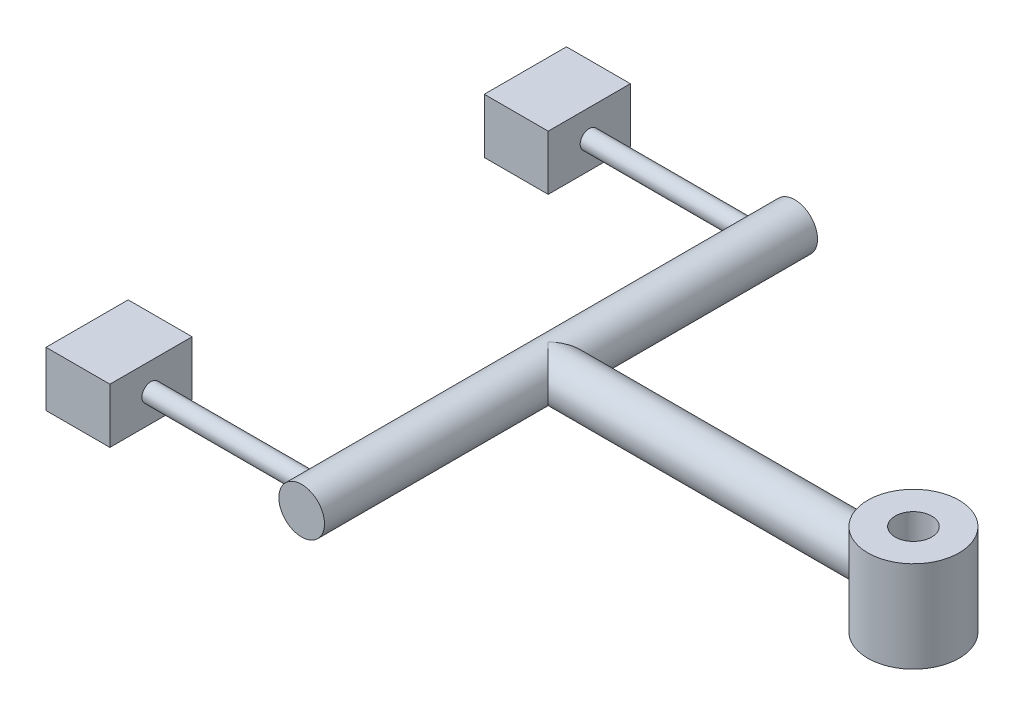
SolidWorks part; units mm, degrees
ref_plane "Front Plane" through (0, 0, 0) normal (0, 0, 1) x (1, 0, 0)
ref_plane "Top Plane" through (0, 0, 0) normal (0, 1, 0) x (1, 0, 0)
ref_plane "Right Plane" through (0, 0, 0) normal (1, 0, 0) x (0, 0, -1)
sketch "Sketch1" plane through (0, 0, 0) normal (0, 1, 0) x (1, 0, 0)
  line L7 (-350, 0) -> (50, 0)
  line L8 (-350, 0) -> (-350, -25)
  line L9 (-350, -25) -> (50, -25)
  line L10 (50, 0) -> (50, -25)
  point P0 (0, 12.5)
  dimension "D1" = 400
  dimension "D3" = 25
revolve "Revolve1" add sketch "Sketch1" angle 360 about L7
sketch "Sketch2" plane through (0, 0, 0) normal (0, 1, 0) x (1, 0, 0)
  line L1 (-350, -270) -> (-375, -270)
  line L2 (-350, -270) -> (-350, 270)
  line L3 (-350, 270) -> (-375, 270)
  line L4 (-375, -270) -> (-375, 270)
  line L5 (-350, -270) -> (-375, 270) construction
  line L6 (-350, 270) -> (-375, -270) construction
  line L7 (-322.6011, 25) -> (-322.6011, -25) construction
  line L10 (50, 25) -> (-350, 25) construction
  line L11 (-350, -25) -> (50, -25) construction
  line L12 (-322.6011, 0) -> (-375, 0) construction
  point P0 (-362.5, 0)
  dimension "D1" = 540
  dimension "D2" = 25
revolve "Revolve2" add sketch "Sketch2" angle 360 about L2
sketch "Sketch4" plane through (0, 0, 0) normal (0, 1, 0) x (1, 0, 0)
  line L0 (50, -25) -> (50, 25) construction
  line L1 (50, 25) -> (50, -25) construction
  line L2 (50, 25) -> (-325, 25) construction
  line L3 (-325, -25) -> (50, -25) construction
  circle A0 centre (50, 0) radius 50
  point P11 (50, 0)
  dimension "D1" = 100
extrude "Boss-Extrude1" add sketch "Sketch4" along normal mid plane 100
sketch "Sketch5" plane through (0, 0, 0) normal (0, 1, 0) x (1, 0, 0)
  line L0 (-350, 240) -> (-550, 240)
  line L1 (-350, -240) -> (-550, -240)
  line L2 (-350, 240) -> (-350, -240) construction
  line L3 (-350, 0) -> (-588.5917, 0) construction
  line L6 (-350, 265) -> (-350, 240) construction
  line L9 (-350, 240) -> (-350, -252.5) construction
  line L11 (-350, 240) -> (-350, 265)
  line L12 (-350, 265) -> (-550, 265)
  line L13 (-550, 240) -> (-550, 265)
  line L14 (-450, 240) -> (-550, 265) construction
  line L15 (-350, 265) -> (-450, 240) construction
  line L16 (-550, -227.5) -> (-350, -227.5)
  line L17 (-550, -227.5) -> (-550, -252.5)
  line L18 (-550, -252.5) -> (-350, -252.5)
  line L19 (-350, -227.5) -> (-350, -252.5)
  line L20 (-550, -227.5) -> (-350, -252.5) construction
  line L21 (-550, -252.5) -> (-350, -227.5) construction
  point P18 (-450, 240)
  point P22 (-450, -240)
  dimension "D1" = 240
  dimension "D2" = 200
  dimension "D3" = 200
  dimension "D4" = 25
  dimension "D5" = 25
revolve "Revolve-Thin1" add sketch "Sketch5" angle 360 about L0
mirror "Mirror2" about plane through (0, 0, 0) normal (0, 0, 1) of "Revolve-Thin1"
sketch "Sketch6" plane through (0, 50, 0) normal (0, 1, 0) x (1, 0, 0)
  circle A0 centre (50, 0) radius 20
extrude "Cut-Extrude1" cut sketch "Sketch6" against normal through all
sketch "Sketch7" plane through (0, 0, 0) normal (0, 1, 0) x (1, 0, 0)
  line L0 (-550, -230) -> (-550, -250) construction
  line L1 (-545, -285) -> (-615, -285)
  line L3 (-545, -195) -> (-615, -195)
  line L4 (-615, -285) -> (-615, -195)
  line L5 (-545, -243.4615) -> (-615, -195) construction
  line L6 (-545, -236.5385) -> (-615, -285) construction
  line L7 (-545, -195) -> (-545, -285)
  point P0 (-550, -240)
  dimension "D1" = 70
  dimension "D2" = 90
  dimension "D3" = 5
extrude "Boss-Extrude2" add sketch "Sketch7" along normal mid plane 60
sketch "Sketch9" plane through (0, 0, 0) normal (0, 1, 0) x (1, 0, 0)
  line L0 (-615, -240) -> (-545, -240) construction
  line L1 (-598, -265) -> (-602, -265)
  line L2 (-595, -262) -> (-595, -221.2245)
  line L3 (-598, -218.2245) -> (-602, -218.2245)
  line L4 (-605, -262) -> (-605, -221.2245)
  line L6 (-575, -281.6122) -> (-615, -281.6122)
  line L7 (-615, -195) -> (-615, -285) construction
  line L8 (-545, -250) -> (-545, -230) construction
  line L14 (-575, -201.6122) -> (-615, -201.6122)
  line L15 (-615, -281.6122) -> (-615, -201.6122)
  line L20 (-575, -281.6122) -> (-615, -201.6122) construction
  line L21 (-575, -201.6122) -> (-615, -281.6122) construction
  line L22 (-575, -201.6122) -> (-555, -201.6122)
  line L24 (-575, -281.6122) -> (-555, -281.6122)
  line L25 (-555, -201.6122) -> (-555, -281.6122)
  arc A0 (-602, -265) -> (-605, -262) centre (-602, -262) cw
  arc A1 (-598, -265) -> (-595, -262) centre (-598, -262) ccw
  arc A2 (-595, -221.2245) -> (-598, -218.2245) centre (-598, -221.2245) ccw
  arc A3 (-602, -218.2245) -> (-605, -221.2245) centre (-602, -221.2245) ccw
  point P0 (-595, -241.6122)
  dimension "D3" = 3
  dimension "D1" = 20
  dimension "D2" = 80
  dimension "D4" = 40
extrude "Cut-Extrude2" cut sketch "Sketch9" against normal mid plane 40
sketch "Sketch10" plane through (-605, 0, 0) normal (-1, 0, 0) x (0, 0, 1)
  line L0 (240, 20) -> (240, -20) construction
  line L1 (266.6128, -10) -> (213.3872, -10)
  line L2 (266.6128, -10) -> (266.6128, 10)
  line L3 (266.6128, 10) -> (213.3872, 10)
  line L4 (213.3872, -10) -> (213.3872, 10)
  line L5 (266.6128, -10) -> (213.3872, 10) construction
  line L6 (266.6128, 10) -> (213.3872, -10) construction
  line L9 (240, 0) -> (214.9764, 0) construction
  point P0 (240, 0)
  dimension "D1" = 20
extrude "Cut-Extrude3" cut sketch "Sketch10" against normal blind 40
mirror "Mirror3" about plane through (0, 0, 0) normal (0, 0, 1) of "Cut-Extrude3", "Boss-Extrude2", "Cut-Extrude2"
